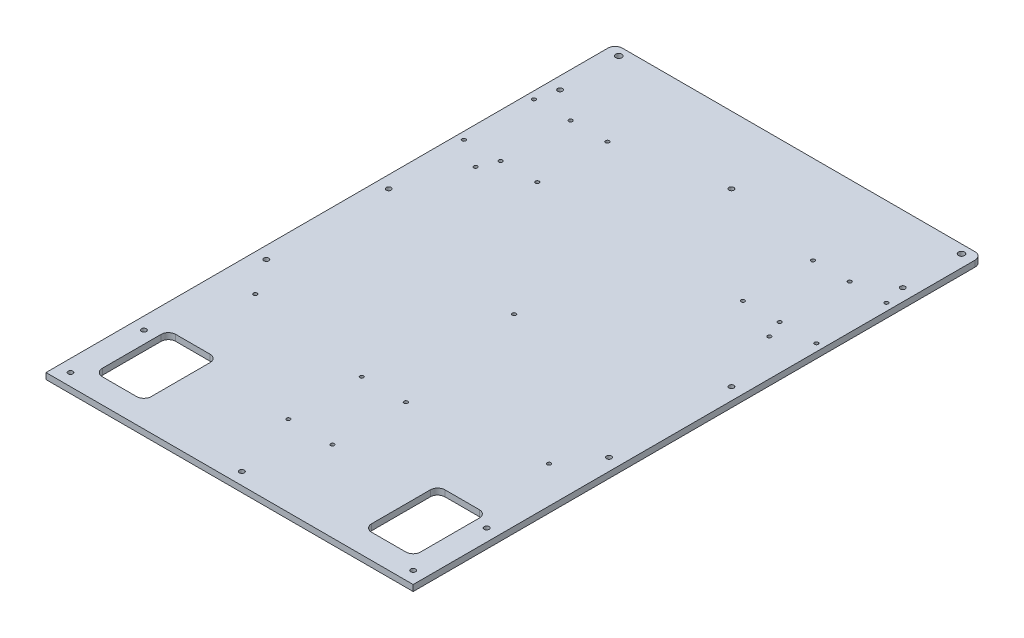
SolidWorks part; units mm, degrees
ref_plane "Front Plane" through (0, 0, 0) normal (0, 0, 1) x (1, 0, 0)
ref_plane "Top Plane" through (0, 0, 0) normal (0, 1, 0) x (1, 0, 0)
ref_plane "Right Plane" through (0, 0, 0) normal (1, 0, 0) x (0, 0, -1)
sketch "Sketch1" plane through (0, 0, 0) normal (0, 1, 0) x (1, 0, 0)
  line L0 (0, -210) -> (0, 210) construction
  line L1 (-150, -210) -> (150, -210)
  line L2 (-150, -210) -> (-150, 210)
  line L3 (-150, 210) -> (150, 210) construction
  line L4 (150, -210) -> (150, 210)
  line L5 (-150, 0) -> (150, 0) construction
  line L6 (-250, 154.9706) -> (0, 404.9706) construction
  line L7 (0, 404.9706) -> (250, 154.9706) construction
  line L8 (-130, -190) -> (-90, -190)
  line L9 (-130, -190) -> (-130, -130)
  line L10 (-130, -130) -> (-90, -130)
  line L11 (-90, -190) -> (-90, -130)
  line L12 (-130, -190) -> (-90, -130) construction
  line L13 (-130, -130) -> (-90, -190) construction
  line L14 (-250, 260) -> (250, 260) construction
  line L15 (-250, 260) -> (-250, -240) construction
  line L16 (-250, -240) -> (250, -240) construction
  line L17 (250, 260) -> (250, -240) construction
  line L18 (-188, 200) -> (-140, 200) construction
  line L19 (-165, 186) -> (-155, 186) construction
  line L20 (-165, 186) -> (-165, 122) construction
  line L21 (-165, 122) -> (-155, 122) construction
  line L22 (-155, 186) -> (-155, 122) construction
  line L23 (-140, 200) -> (-140, 248) construction
  line L24 (-140, 210) -> (-140, -210) construction
  line L25 (-150, -200) -> (150, -200) construction
  line L26 (-130, -160) -> (-90, -160) construction
  line L27 (-110, -190) -> (-110, -130) construction
  line L28 (-140, 248) -> (150, 248) construction
  line L29 (-140, 200) -> (0, 200) construction
  line L30 (0, 182.625) -> (-150, 182.625) construction
  line L31 (130, -190) -> (90, -190)
  line L32 (130, -190) -> (130, -130)
  line L33 (130, -130) -> (90, -130)
  line L34 (90, -190) -> (90, -130)
  line L35 (-200, -205) -> (-200, 200) construction
  line L36 (-155, 154) -> (0, 154) construction
  line L37 (-150, 190) -> (0, 190) construction
  line L38 (-150, 118) -> (0, 118) construction
  line L39 (-150, 210) -> (-150, 255)
  line L40 (-150, 255) -> (150, 255)
  line L41 (150, 255) -> (150, 210)
  circle A0 centre (-140, 248) radius 12 construction
  circle A1 centre (-188, 200) radius 12 construction
  circle A2 centre (-188, -205) radius 12 construction
  circle A3 centre (0, -200) radius 2
  circle A4 centre (-140, -200) radius 2
  circle A15 centre (-140, -40) radius 2
  circle A16 centre (-140, 60) radius 2
  circle A30 centre (140, -200) radius 2
  circle A31 centre (-114, 182.625) radius 1.5
  circle A32 centre (-144, 182.625) radius 1.5
  circle A33 centre (-84, 182.625) radius 1.5
  circle A34 centre (-84, 125.375) radius 1.5
  circle A35 centre (-114, 125.375) radius 1.5
  circle A36 centre (-144, 125.375) radius 1.5
  circle A37 centre (-140, -140) radius 2
  circle A38 centre (-140, 248) radius 2.5
  circle A40 centre (140, -140) radius 2
  circle A41 centre (140, -200) radius 2
  circle A42 centre (140, 60) radius 2
  circle A43 centre (140, -40) radius 2
  circle A44 centre (144, 125.375) radius 1.5
  circle A45 centre (114, 125.375) radius 1.5
  circle A46 centre (84, 125.375) radius 1.5
  circle A47 centre (84, 182.625) radius 1.5
  circle A48 centre (144, 182.625) radius 1.5
  circle A49 centre (114, 182.625) radius 1.5
  circle A52 centre (140, 248) radius 2.5
  circle A53 centre (-140, 200) radius 2
  circle A54 centre (0, 200) radius 2
  circle A55 centre (140, 200) radius 2
  point P0 (0, 0)
  point P8 (-110, -160)
  point P17 (0, -240)
  dimension "D15" = 24
  dimension "D16" = 10
  dimension "D22" = 50
  dimension "D23" = 5
  dimension "D25" = 4
  dimension "D27" = 36
  dimension "D28" = 30
  dimension "D29" = 200
  dimension "D31" = 4
  dimension "D33" = 100
  dimension "D34" = 30
  dimension "D35" = 36
  dimension "D37" = 3
  dimension "D38" = 57.25
  dimension "D20" = 4
  dimension "D21" = 100
  dimension "D1" = 300
  dimension "D2" = 420
  dimension "D3" = 60
  dimension "D4" = 40
  dimension "D5" = 20
  dimension "D6" = 20
  dimension "D7" = 500
  dimension "D8" = 500
  dimension "D9" = 45
  dimension "D10" = 45
  dimension "D11" = 50
  dimension "D12" = 64
  dimension "D13" = 10
  dimension "D14" = 5
  dimension "D17" = 5
  dimension "D18" = 10
  dimension "D19" = 10
  dimension "D26" = 20
  dimension "D36" = 36
  dimension "D39" = 45
  dimension "D40" = 58
extrude "Boss-Extrude1" add sketch "Sketch1" along normal blind 5
fillet "Fillet1" radius 6 10 edges at (-130, 2.5, 130) (150, 2.5, -255) (-150, 2.5, -255) (130, 2.5, 190) (130, 2.5, 130) (90, 2.5, 130) (90, 2.5, 190) (-130, 2.5, 190) (-90, 2.5, 190) (-90, 2.5, 130)
sketch "Sketch2" plane through (0, 5, 0) normal (0, 1, 0) x (1, 0, 0)
  line L0 (0, -210) -> (0, 255) construction
  line L1 (-150, -210) -> (150, -210) construction
  line L2 (-144, 255) -> (144, 255) construction
  line L8 (18, -84) -> (18, -144) construction
  line L9 (-24, -78) -> (24, -78) construction
  line L10 (-24, -78) -> (-24, -150) construction
  line L15 (-24, -150) -> (24, -150) construction
  line L16 (24, -78) -> (24, -150) construction
  line L17 (-24, -78) -> (24, -150) construction
  line L18 (-24, -150) -> (24, -78) construction
  line L19 (-18, -144) -> (18, -144) construction
  line L20 (-18, -84) -> (-18, -144) construction
  line L21 (-18, -84) -> (18, -84) construction
  line L31 (-120, 111) -> (120, 111) construction
  line L32 (-120, 111) -> (-120, -69) construction
  line L33 (-120, -69) -> (120, -69) construction
  line L34 (120, 111) -> (120, -69) construction
  line L35 (-120, 111) -> (120, -69) construction
  line L36 (-120, -69) -> (120, 111) construction
  circle A6 centre (-18, -144) radius 1.5
  circle A7 centre (18, -144) radius 1.5
  circle A8 centre (18, -84) radius 1.5
  circle A9 centre (-18, -84) radius 1.5
  circle A10 centre (-120, -69) radius 1.5
  circle A11 centre (120, -69) radius 1.5
  circle A12 centre (120, 111) radius 1.5
  circle A13 centre (-120, 111) radius 1.5
  circle A14 centre (0, 22.5) radius 1.5
  point P6 (0, -114)
  point P19 (0, 21)
  dimension "D5" = 60
  dimension "D7" = 180
  dimension "D4" = 3
  dimension "D1" = 48
  dimension "D2" = 72
  dimension "D3" = 6
  dimension "D6" = 240
  dimension "D8" = 21
extrude "Cut-Extrude1" cut sketch "Sketch2" against normal through all
